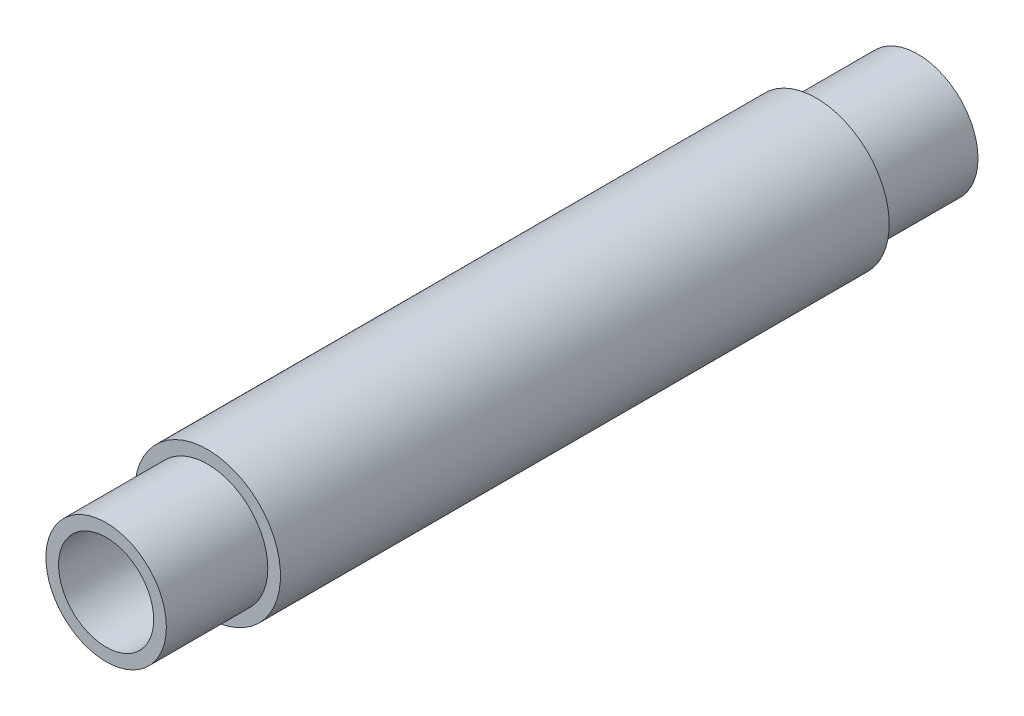
SolidWorks part; units mm, degrees
ref_plane "Front Plane" through (0, 0, 0) normal (0, 0, 1) x (1, 0, 0)
ref_plane "Top Plane" through (0, 0, 0) normal (0, 1, 0) x (1, 0, 0)
ref_plane "Right Plane" through (0, 0, 0) normal (1, 0, 0) x (0, 0, -1)
sketch "Sketch1" plane through (0, 0, 0) normal (0, 0, 1) x (1, 0, 0)
  circle A0 centre (0, 0) radius 15.0812
  circle A1 centre (0, 0) radius 11.9062
  dimension "D1" = 30.1625
  dimension "D2" = 3.175
extrude "Boss-Extrude1" add sketch "Sketch1" along normal mid plane 203.2
sketch "Sketch2" plane through (0, 0, 0) normal (0, 0, 1) x (1, 0, 0)
  circle A0 centre (0, 0) radius 18.2562
  circle A1 centre (0, 0) radius 11.9062
  circle A2 centre (0, 0) radius 11.9062 construction
  circle A3 centre (0, 0) radius 15.0812 construction
  dimension "D1" = 3.175
extrude "Boss-Extrude2" add sketch "Sketch2" along normal mid plane 152.4 contours A0 | A1
